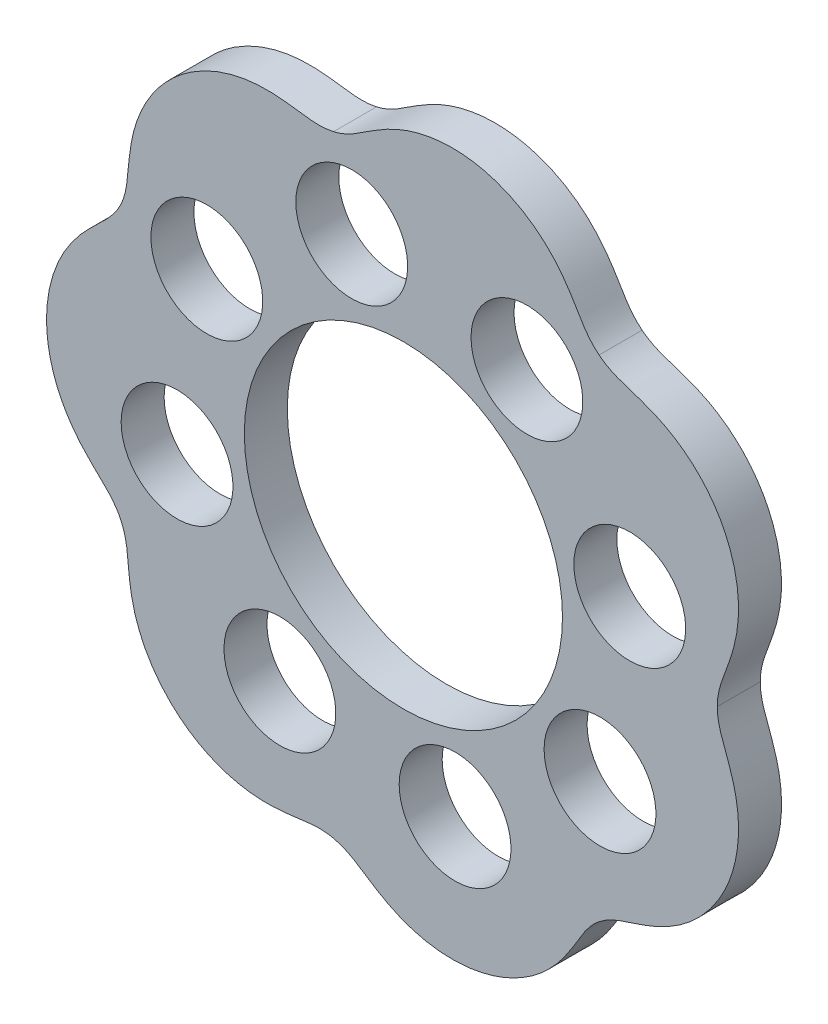
SolidWorks part; units mm, degrees
material "5052-H34"
ref_plane "Front Plane" through (0, 0, 0) normal (0, 0, 1) x (1, 0, 0)
ref_plane "Top Plane" through (0, 0, 0) normal (0, 1, 0) x (1, 0, 0)
ref_plane "Right Plane" through (0, 0, 0) normal (1, 0, 0) x (0, 0, -1)
sketch "Sketch1" plane through (0, 0, 0) normal (0, 0, 1) x (1, 0, 0)
  line L0 (0, 0) -> (37, 0) construction
  line L2 (37, 0) -> (39.5, 0) construction
  line L5 (24.6278, 30.8823) -> (0, 0) construction
  line L6 (0, 0) -> (-8.7896, 38.5096) construction
  line L7 (-35.5883, 17.1384) -> (0, 0) construction
  line L9 (-35.5883, -17.1384) -> (0, 0) construction
  line L10 (-8.7896, -38.5097) -> (0, 0) construction
  line L11 (24.6278, -30.8823) -> (0, 0) construction
  circle A0 centre (0, 0) radius 36 construction
  circle A1 centre (37, 0) radius 6 construction
  spline S0 degree 4 poles (39.9483, -2.12) (39.9195, -2.0383) (39.8632, -1.8746) (39.7822, -1.6278) (39.6848, -1.2955) (39.6113, -0.995) (39.5602, -0.7266) (39.5276, -0.4967) (39.5088, -0.2963) (39.4998, -0.0928) (39.4991, 0.0501) (39.505, 0.2155) (39.5157, 0.3724) (39.5329, 0.5353) (39.558, 0.7077) (39.6011, 0.9443) (39.6734, 1.255) (39.779, 1.6227) (39.9203, 2.0472) (40.0768, 2.4805) (40.3026, 3.083) (40.5945, 3.8559) (41.0315, 5.0877) (41.5249, 6.8077) (41.9013, 8.8642) (42.0339, 11.2502) (41.8633, 13.6337) (41.3936, 15.9767) (40.6339, 18.2422) (39.5972, 20.395) (38.2996, 22.4015) (36.7607, 24.2296) (35.0035, 25.849) (33.2989, 27.0601) (31.7392, 27.9386) (30.3866, 28.5643) (29.2788, 29.0047) (28.3249, 29.3341) (27.5386, 29.5876) (26.9268, 29.7867) (26.4905, 29.9345) (26.0706, 30.0887) (25.717, 30.2355) (25.4294, 30.3725) (25.184, 30.5045) (25.0052, 30.6109) (24.8304, 30.7289) (24.6664, 30.8504) (24.5552, 30.94) (24.4016, 31.074) (24.2567, 31.2136) (24.0973, 31.3824) (23.9194, 31.5897) (23.7303, 31.8345) (23.5312, 32.1179) (23.3886, 32.3351) (23.2958, 32.4812) (23.2499, 32.5546) knots 0 0 0 0 0 0.00783 0.015661 0.023491 0.031321 0.035802 0.040282 0.044763 0.049243 0.052611 0.055979 0.059347 0.062715 0.06731 0.071905 0.081096 0.091513 0.101931 0.112349 0.122766 0.149711 0.176657 0.230547 0.284438 0.338328 0.392219 0.446109 0.5 0.553891 0.607781 0.661672 0.715562 0.769453 0.796398 0.823343 0.850289 0.877234 0.887651 0.898069 0.908487 0.918904 0.928095 0.93269 0.937285 0.944021 0.947389 0.950757 0.955237 0.959718 0.964198 0.968679 0.976509 0.984339 0.99217 1 1 1 1 1 construction
  spline S1 degree 4 poles (39.5, 0) (39.5, 0.0336) (39.5009, 0.1009) (39.505, 0.2155) (39.5157, 0.3724) (39.5329, 0.5353) (39.558, 0.7077) (39.6011, 0.9443) (39.6734, 1.255) (39.779, 1.6227) (39.9203, 2.0472) (40.0768, 2.4805) (40.3026, 3.083) (40.5945, 3.8559) (41.0315, 5.0877) (41.5249, 6.8077) (41.9013, 8.8642) (42.0339, 11.2502) (41.8633, 13.6337) (41.3936, 15.9767) (40.6339, 18.2422) (39.5972, 20.395) (38.2996, 22.4015) (36.7607, 24.2296) (35.0035, 25.849) (33.2989, 27.0601) (31.7392, 27.9386) (30.3866, 28.5643) (29.2788, 29.0047) (28.3249, 29.3341) (27.5386, 29.5876) (26.9268, 29.7867) (26.4905, 29.9345) (26.0706, 30.0887) (25.717, 30.2355) (25.4294, 30.3725) (25.184, 30.5045) (25.0052, 30.6109) (24.8304, 30.7289) (24.7073, 30.8201) (24.6541, 30.8614) (24.6278, 30.8823) knots 0.049243 0.049243 0.049243 0.049243 0.049243 0.052611 0.055979 0.059347 0.062715 0.06731 0.071905 0.081096 0.091513 0.101931 0.112349 0.122766 0.149711 0.176657 0.230547 0.284438 0.338328 0.392219 0.446109 0.5 0.553891 0.607781 0.661672 0.715562 0.769453 0.796398 0.823343 0.850289 0.877234 0.887651 0.898069 0.908487 0.918904 0.928095 0.93269 0.937285 0.944021 0.947389 0.950757 0.950757 0.950757 0.950757 0.950757 construction
  spline S2 degree 4 poles (23.2499, -32.5546) (23.2958, -32.4812) (23.3886, -32.3351) (23.5312, -32.1179) (23.7303, -31.8345) (23.9194, -31.5897) (24.0973, -31.3824) (24.2568, -31.2136) (24.4016, -31.074) (24.5552, -30.9401) (24.6665, -30.8504) (24.7994, -30.7519) (24.9287, -30.6624) (25.0669, -30.5743) (25.2173, -30.4865) (25.4292, -30.3727) (25.7171, -30.2354) (26.0705, -30.0887) (26.4905, -29.9345) (26.9268, -29.7867) (27.5387, -29.5876) (28.3249, -29.334) (29.5605, -28.9076) (31.2128, -28.2209) (33.0554, -27.233) (35.0035, -25.8491) (36.7607, -24.2296) (38.2996, -22.4016) (39.5971, -20.395) (40.6339, -18.2422) (41.3936, -15.9767) (41.8634, -13.6337) (42.0339, -11.2502) (41.9179, -9.1625) (41.6323, -7.3953) (41.2783, -5.9477) (40.9318, -4.807) (40.5946, -3.8558) (40.3026, -3.083) (40.0768, -2.4805) (39.9203, -2.0472) (39.779, -1.6228) (39.6734, -1.2549) (39.6011, -0.9446) (39.5513, -0.6704) (39.523, -0.4642) (39.5063, -0.254) (39.4991, -0.05) (39.4998, 0.0928) (39.5088, 0.2963) (39.5276, 0.4967) (39.5602, 0.7266) (39.6113, 0.995) (39.6848, 1.2955) (39.7822, 1.6278) (39.8632, 1.8746) (39.9195, 2.0383) (39.9483, 2.12) knots 0 0 0 0 0 0.00783 0.015661 0.023491 0.031321 0.035802 0.040282 0.044763 0.049243 0.052611 0.055979 0.059347 0.062715 0.06731 0.071905 0.081096 0.091513 0.101931 0.112349 0.122766 0.149711 0.176657 0.230547 0.284438 0.338328 0.392219 0.446109 0.5 0.553891 0.607781 0.661672 0.715562 0.769453 0.796398 0.823343 0.850289 0.877234 0.887651 0.898069 0.908487 0.918904 0.928095 0.93269 0.937285 0.944021 0.947389 0.950757 0.955237 0.959718 0.964198 0.968679 0.976509 0.984339 0.99217 1 1 1 1 1 construction
  spline S3 degree 4 poles (24.6278, -30.8823) (24.6541, -30.8614) (24.7073, -30.8201) (24.7994, -30.7519) (24.9287, -30.6624) (25.0669, -30.5743) (25.2173, -30.4865) (25.4292, -30.3727) (25.7171, -30.2354) (26.0705, -30.0887) (26.4905, -29.9345) (26.9268, -29.7867) (27.5387, -29.5876) (28.3249, -29.334) (29.5605, -28.9076) (31.2128, -28.2209) (33.0554, -27.233) (35.0035, -25.8491) (36.7607, -24.2296) (38.2996, -22.4016) (39.5971, -20.395) (40.6339, -18.2422) (41.3936, -15.9767) (41.8634, -13.6337) (42.0339, -11.2502) (41.9179, -9.1625) (41.6323, -7.3953) (41.2783, -5.9477) (40.9318, -4.807) (40.5946, -3.8558) (40.3026, -3.083) (40.0768, -2.4805) (39.9203, -2.0472) (39.779, -1.6228) (39.6734, -1.2549) (39.6011, -0.9446) (39.5513, -0.6704) (39.523, -0.4642) (39.5063, -0.254) (39.5009, -0.1009) (39.5, -0.0336) (39.5, 0) knots 0.049243 0.049243 0.049243 0.049243 0.049243 0.052611 0.055979 0.059347 0.062715 0.06731 0.071905 0.081096 0.091513 0.101931 0.112349 0.122766 0.149711 0.176657 0.230547 0.284438 0.338328 0.392219 0.446109 0.5 0.553891 0.607781 0.661672 0.715562 0.769453 0.796398 0.823343 0.850289 0.877234 0.887651 0.898069 0.908487 0.918904 0.928095 0.93269 0.937285 0.944021 0.947389 0.950757 0.950757 0.950757 0.950757 0.950757 construction
  spline S4 degree 4 poles (-10.9562, -38.475) (-10.8702, -38.4651) (-10.698, -38.4466) (-10.4393, -38.4226) (-10.0937, -38.4016) (-9.7844, -38.3968) (-9.5114, -38.4066) (-9.2799, -38.426) (-9.0804, -38.4523) (-8.88, -38.4888) (-8.7405, -38.5199) (-8.5806, -38.5624) (-8.43, -38.6078) (-8.275, -38.6609) (-8.1126, -38.7237) (-7.8915, -38.8184) (-7.6046, -38.9579) (-7.2696, -39.1427) (-6.8872, -39.375) (-6.4996, -39.6239) (-5.9625, -39.9782) (-5.2739, -40.4348) (-4.1702, -41.1349) (-2.6031, -41.9986) (-0.6819, -42.8232) (1.6147, -43.4834) (3.9765, -43.8475) (6.3652, -43.911) (8.7429, -43.6744) (11.0725, -43.1427) (13.3174, -42.3241) (15.4421, -41.2306) (17.4119, -39.8778) (18.9719, -38.4855) (20.1754, -37.1604) (21.0865, -35.981) (21.7623, -34.9989) (22.2957, -34.1422) (22.7178, -33.432) (23.0481, -32.8798) (23.2893, -32.4874) (23.5331, -32.1123) (23.7549, -31.8003) (23.9524, -31.5503) (24.1357, -31.3404) (24.2793, -31.1898) (24.4332, -31.0457) (24.5882, -30.9128) (24.7002, -30.8243) (24.865, -30.7045) (25.0333, -30.5943) (25.2335, -30.4763) (25.4752, -30.3491) (25.7559, -30.2191) (26.0764, -30.0881) (26.3199, -29.9975) (26.4831, -29.9395) (26.5648, -29.9111) knots 0 0 0 0 0 0.00783 0.015661 0.023491 0.031321 0.035802 0.040282 0.044763 0.049243 0.052611 0.055979 0.059347 0.062715 0.06731 0.071905 0.081096 0.091513 0.101931 0.112349 0.122766 0.149711 0.176657 0.230547 0.284438 0.338328 0.392219 0.446109 0.5 0.553891 0.607781 0.661672 0.715562 0.769453 0.796398 0.823343 0.850289 0.877234 0.887651 0.898069 0.908487 0.918904 0.928095 0.93269 0.937285 0.944021 0.947389 0.950757 0.955237 0.959718 0.964198 0.968679 0.976509 0.984339 0.99217 1 1 1 1 1 construction
  spline S5 degree 4 poles (-8.7896, -38.5097) (-8.7568, -38.5171) (-8.6914, -38.533) (-8.5806, -38.5624) (-8.43, -38.6078) (-8.275, -38.6609) (-8.1126, -38.7237) (-7.8915, -38.8184) (-7.6046, -38.9579) (-7.2696, -39.1427) (-6.8872, -39.375) (-6.4996, -39.6239) (-5.9625, -39.9782) (-5.2739, -40.4348) (-4.1702, -41.1349) (-2.6031, -41.9986) (-0.6819, -42.8232) (1.6147, -43.4834) (3.9765, -43.8475) (6.3652, -43.911) (8.7429, -43.6744) (11.0725, -43.1427) (13.3174, -42.3241) (15.4421, -41.2306) (17.4119, -39.8778) (18.9719, -38.4855) (20.1754, -37.1604) (21.0865, -35.981) (21.7623, -34.9989) (22.2957, -34.1422) (22.7178, -33.432) (23.0481, -32.8798) (23.2893, -32.4874) (23.5331, -32.1123) (23.7549, -31.8003) (23.9524, -31.5503) (24.1357, -31.3404) (24.2793, -31.1898) (24.4332, -31.0457) (24.5495, -30.946) (24.6016, -30.9033) (24.6278, -30.8823) knots 0.049243 0.049243 0.049243 0.049243 0.049243 0.052611 0.055979 0.059347 0.062715 0.06731 0.071905 0.081096 0.091513 0.101931 0.112349 0.122766 0.149711 0.176657 0.230547 0.284438 0.338328 0.392219 0.446109 0.5 0.553891 0.607781 0.661672 0.715562 0.769453 0.796398 0.823343 0.850289 0.877234 0.887651 0.898069 0.908487 0.918904 0.928095 0.93269 0.937285 0.944021 0.947389 0.950757 0.950757 0.950757 0.950757 0.950757 construction
  spline S6 degree 4 poles (-36.912, -15.4229) (-36.8506, -15.484) (-36.7288, -15.607) (-36.5488, -15.7943) (-36.3169, -16.0514) (-36.1203, -16.2903) (-35.9578, -16.5098) (-35.8286, -16.7029) (-35.7247, -16.8752) (-35.6284, -17.0547) (-35.5657, -17.1832) (-35.4992, -17.3347) (-35.4408, -17.4807) (-35.3857, -17.635) (-35.3335, -17.8012) (-35.2697, -18.0331) (-35.1999, -18.3443) (-35.1356, -18.7215) (-35.0787, -19.1653) (-35.0317, -19.6235) (-34.9737, -20.2643) (-34.9014, -21.0873) (-34.7606, -22.3868) (-34.4588, -24.1505) (-33.9057, -26.1667) (-32.99, -28.3739) (-31.8021, -30.4474) (-30.3624, -32.3545) (-28.6949, -34.066) (-26.8267, -35.5559) (-24.7871, -36.8007) (-22.6074, -37.78) (-20.3215, -38.4766) (-18.2604, -38.8281) (-16.474, -38.9429) (-14.9838, -38.9199) (-13.7946, -38.8359) (-12.7923, -38.7188) (-11.9739, -38.606) (-11.3362, -38.52) (-10.879, -38.4639) (-10.4338, -38.4206) (-10.0516, -38.3994) (-9.733, -38.3981) (-9.4546, -38.4105) (-9.2473, -38.4288) (-9.0386, -38.4593) (-8.8382, -38.4976) (-8.6991, -38.5301) (-8.5026, -38.5841) (-8.3115, -38.6471) (-8.0946, -38.73) (-7.8443, -38.8396) (-7.5677, -38.9781) (-7.2654, -39.147) (-7.0428, -39.2809) (-6.8957, -39.3722) (-6.8225, -39.4185) knots 0 0 0 0 0 0.00783 0.015661 0.023491 0.031321 0.035802 0.040282 0.044763 0.049243 0.052611 0.055979 0.059347 0.062715 0.06731 0.071905 0.081096 0.091513 0.101931 0.112349 0.122766 0.149711 0.176657 0.230547 0.284438 0.338328 0.392219 0.446109 0.5 0.553891 0.607781 0.661672 0.715562 0.769453 0.796398 0.823343 0.850289 0.877234 0.887651 0.898069 0.908487 0.918904 0.928095 0.93269 0.937285 0.944021 0.947389 0.950757 0.955237 0.959718 0.964198 0.968679 0.976509 0.984339 0.99217 1 1 1 1 1 construction
  spline S7 degree 4 poles (-35.5883, -17.1384) (-35.5737, -17.1687) (-35.5453, -17.2297) (-35.4992, -17.3347) (-35.4408, -17.4807) (-35.3857, -17.635) (-35.3335, -17.8012) (-35.2697, -18.0331) (-35.1999, -18.3443) (-35.1356, -18.7215) (-35.0787, -19.1653) (-35.0317, -19.6235) (-34.9737, -20.2643) (-34.9014, -21.0873) (-34.7606, -22.3868) (-34.4588, -24.1505) (-33.9057, -26.1667) (-32.99, -28.3739) (-31.8021, -30.4474) (-30.3624, -32.3545) (-28.6949, -34.066) (-26.8267, -35.5559) (-24.7871, -36.8007) (-22.6074, -37.78) (-20.3215, -38.4766) (-18.2604, -38.8281) (-16.474, -38.9429) (-14.9838, -38.9199) (-13.7946, -38.8359) (-12.7923, -38.7188) (-11.9739, -38.606) (-11.3362, -38.52) (-10.879, -38.4639) (-10.4338, -38.4206) (-10.0516, -38.3994) (-9.733, -38.3981) (-9.4546, -38.4105) (-9.2473, -38.4288) (-9.0386, -38.4593) (-8.8882, -38.4881) (-8.8223, -38.5022) (-8.7896, -38.5097) knots 0.049243 0.049243 0.049243 0.049243 0.049243 0.052611 0.055979 0.059347 0.062715 0.06731 0.071905 0.081096 0.091513 0.101931 0.112349 0.122766 0.149711 0.176657 0.230547 0.284438 0.338328 0.392219 0.446109 0.5 0.553891 0.607781 0.661672 0.715562 0.769453 0.796398 0.823343 0.850289 0.877234 0.887651 0.898069 0.908487 0.918904 0.928095 0.93269 0.937285 0.944021 0.947389 0.950757 0.950757 0.950757 0.950757 0.950757 construction
  spline S8 degree 4 poles (-35.0725, 19.243) (-35.0819, 19.1569) (-35.1022, 18.985) (-35.1364, 18.7274) (-35.1928, 18.3858) (-35.257, 18.0831) (-35.3273, 17.8192) (-35.3977, 17.5978) (-35.4677, 17.4092) (-35.5479, 17.2219) (-35.6093, 17.0929) (-35.6863, 16.9464) (-35.764, 16.8097) (-35.8503, 16.6704) (-35.9477, 16.526) (-36.0892, 16.3315) (-36.2891, 16.0829) (-36.5438, 15.7974) (-36.8553, 15.4763) (-37.1842, 15.1538) (-37.6491, 14.7089) (-38.2475, 14.1393) (-39.1757, 13.219) (-40.3664, 11.8834) (-41.5979, 10.1939) (-42.7526, 8.1018) (-43.6331, 5.8802) (-44.2264, 3.5655) (-44.5249, 1.1947) (-44.5249, -1.1948) (-44.2264, -3.5655) (-43.6331, -5.8803) (-42.7525, -8.1018) (-41.7422, -9.9324) (-40.7182, -11.4006) (-39.771, -12.5513) (-38.9639, -13.4287) (-38.2475, -14.1394) (-37.649, -14.7089) (-37.1842, -15.1538) (-36.8552, -15.4763) (-36.5438, -15.7974) (-36.2889, -16.083) (-36.0892, -16.3313) (-35.9254, -16.5567) (-35.8105, -16.7302) (-35.7042, -16.9123) (-35.6092, -17.0929) (-35.5478, -17.2219) (-35.4676, -17.4092) (-35.3976, -17.5978) (-35.3272, -17.8192) (-35.2569, -18.0831) (-35.1927, -18.3858) (-35.1363, -18.7274) (-35.1021, -18.985) (-35.0818, -19.1569) (-35.0724, -19.243) knots 0 0 0 0 0 0.00783 0.015661 0.023491 0.031321 0.035802 0.040282 0.044763 0.049243 0.052611 0.055979 0.059347 0.062715 0.06731 0.071905 0.081096 0.091513 0.101931 0.112349 0.122766 0.149711 0.176657 0.230547 0.284438 0.338328 0.392219 0.446109 0.5 0.553891 0.607781 0.661672 0.715562 0.769453 0.796398 0.823343 0.850289 0.877234 0.887651 0.898069 0.908487 0.918904 0.928095 0.93269 0.937285 0.944021 0.947389 0.950757 0.955237 0.959718 0.964198 0.968679 0.976509 0.984339 0.99217 1 1 1 1 1 construction
  spline S9 degree 4 poles (-35.5883, 17.1384) (-35.6029, 17.1082) (-35.6329, 17.0479) (-35.6863, 16.9464) (-35.764, 16.8097) (-35.8503, 16.6704) (-35.9477, 16.526) (-36.0892, 16.3315) (-36.2891, 16.0829) (-36.5438, 15.7974) (-36.8553, 15.4763) (-37.1842, 15.1538) (-37.6491, 14.7089) (-38.2475, 14.1393) (-39.1757, 13.219) (-40.3664, 11.8834) (-41.5979, 10.1939) (-42.7526, 8.1018) (-43.6331, 5.8802) (-44.2264, 3.5655) (-44.5249, 1.1947) (-44.5249, -1.1948) (-44.2264, -3.5655) (-43.6331, -5.8803) (-42.7525, -8.1018) (-41.7422, -9.9324) (-40.7182, -11.4006) (-39.771, -12.5513) (-38.9639, -13.4287) (-38.2475, -14.1394) (-37.649, -14.7089) (-37.1842, -15.1538) (-36.8552, -15.4763) (-36.5438, -15.7974) (-36.2889, -16.083) (-36.0892, -16.3313) (-35.9254, -16.5567) (-35.8105, -16.7302) (-35.7042, -16.9123) (-35.6329, -17.0479) (-35.6028, -17.1082) (-35.5883, -17.1384) knots 0.049243 0.049243 0.049243 0.049243 0.049243 0.052611 0.055979 0.059347 0.062715 0.06731 0.071905 0.081096 0.091513 0.101931 0.112349 0.122766 0.149711 0.176657 0.230547 0.284438 0.338328 0.392219 0.446109 0.5 0.553891 0.607781 0.661672 0.715562 0.769453 0.796398 0.823343 0.850289 0.877234 0.887651 0.898069 0.908487 0.918904 0.928095 0.93269 0.937285 0.944021 0.947389 0.950757 0.950757 0.950757 0.950757 0.950757 construction
  spline S10 degree 4 poles (-6.8225, 39.4184) (-6.8957, 39.3722) (-7.0428, 39.2808) (-7.2654, 39.1469) (-7.5677, 38.978) (-7.8444, 38.8395) (-8.0946, 38.7299) (-8.3115, 38.647) (-8.5027, 38.5841) (-8.6991, 38.53) (-8.8382, 38.4976) (-9.0008, 38.4665) (-9.1561, 38.442) (-9.3188, 38.4226) (-9.4924, 38.4087) (-9.7327, 38.3981) (-10.0517, 38.3993) (-10.4337, 38.4205) (-10.879, 38.4638) (-11.3362, 38.5199) (-11.9739, 38.606) (-12.7923, 38.7187) (-14.0905, 38.8706) (-15.8772, 38.9688) (-17.9659, 38.8782) (-20.3216, 38.4766) (-22.6074, 37.7799) (-24.7871, 36.8006) (-26.8267, 35.5558) (-28.6949, 34.066) (-30.3624, 32.3545) (-31.8022, 30.4474) (-32.99, 28.3739) (-33.7914, 26.4426) (-34.3008, 24.7266) (-34.6099, 23.2686) (-34.7927, 22.0906) (-34.9016, 21.0873) (-34.9737, 20.2643) (-35.0318, 19.6235) (-35.0788, 19.1652) (-35.1356, 18.7215) (-35.2001, 18.3442) (-35.2696, 18.0333) (-35.3437, 17.7647) (-35.4077, 17.5667) (-35.4838, 17.37) (-35.5658, 17.1831) (-35.6284, 17.0547) (-35.7248, 16.8752) (-35.8287, 16.7029) (-35.9578, 16.5098) (-36.1204, 16.2903) (-36.3169, 16.0514) (-36.5489, 15.7943) (-36.7289, 15.607) (-36.8507, 15.484) (-36.9121, 15.4229) knots 0 0 0 0 0 0.00783 0.015661 0.023491 0.031321 0.035802 0.040282 0.044763 0.049243 0.052611 0.055979 0.059347 0.062715 0.06731 0.071905 0.081096 0.091513 0.101931 0.112349 0.122766 0.149711 0.176657 0.230547 0.284438 0.338328 0.392219 0.446109 0.5 0.553891 0.607781 0.661672 0.715562 0.769453 0.796398 0.823343 0.850289 0.877234 0.887651 0.898069 0.908487 0.918904 0.928095 0.93269 0.937285 0.944021 0.947389 0.950757 0.955237 0.959718 0.964198 0.968679 0.976509 0.984339 0.99217 1 1 1 1 1 construction
  spline S11 degree 4 poles (-8.7896, 38.5096) (-8.8223, 38.5021) (-8.8882, 38.488) (-9.0008, 38.4665) (-9.1561, 38.442) (-9.3188, 38.4226) (-9.4924, 38.4087) (-9.7327, 38.3981) (-10.0517, 38.3993) (-10.4337, 38.4205) (-10.879, 38.4638) (-11.3362, 38.5199) (-11.9739, 38.606) (-12.7923, 38.7187) (-14.0905, 38.8706) (-15.8772, 38.9688) (-17.9659, 38.8782) (-20.3216, 38.4766) (-22.6074, 37.7799) (-24.7871, 36.8006) (-26.8267, 35.5558) (-28.6949, 34.066) (-30.3624, 32.3545) (-31.8022, 30.4474) (-32.99, 28.3739) (-33.7914, 26.4426) (-34.3008, 24.7266) (-34.6099, 23.2686) (-34.7927, 22.0906) (-34.9016, 21.0873) (-34.9737, 20.2643) (-35.0318, 19.6235) (-35.0788, 19.1652) (-35.1356, 18.7215) (-35.2001, 18.3442) (-35.2696, 18.0333) (-35.3437, 17.7647) (-35.4077, 17.5667) (-35.4838, 17.37) (-35.5454, 17.2297) (-35.5738, 17.1687) (-35.5883, 17.1384) knots 0.049243 0.049243 0.049243 0.049243 0.049243 0.052611 0.055979 0.059347 0.062715 0.06731 0.071905 0.081096 0.091513 0.101931 0.112349 0.122766 0.149711 0.176657 0.230547 0.284438 0.338328 0.392219 0.446109 0.5 0.553891 0.607781 0.661672 0.715562 0.769453 0.796398 0.823343 0.850289 0.877234 0.887651 0.898069 0.908487 0.918904 0.928095 0.93269 0.937285 0.944021 0.947389 0.950757 0.950757 0.950757 0.950757 0.950757 construction
  spline S12 degree 4 poles (26.5648, 29.9111) (26.4831, 29.9395) (26.3199, 29.9975) (26.0764, 30.0881) (25.7559, 30.2191) (25.4752, 30.3491) (25.2335, 30.4763) (25.0333, 30.5943) (24.865, 30.7045) (24.7003, 30.8243) (24.5881, 30.9129) (24.4624, 31.0206) (24.3465, 31.1268) (24.2299, 31.2418) (24.1107, 31.3689) (23.9526, 31.5502) (23.7547, 31.8004) (23.5331, 32.1122) (23.2893, 32.4874) (23.0481, 32.8798) (22.7179, 33.4321) (22.2956, 34.1422) (21.605, 35.2519) (20.5678, 36.71) (19.1947, 38.2865) (17.412, 39.8778) (15.4421, 41.2306) (13.3174, 42.3241) (11.0725, 43.1427) (8.7429, 43.6744) (6.3651, 43.9109) (3.9764, 43.8475) (1.6147, 43.4834) (-0.3949, 42.9058) (-2.0542, 42.2341) (-3.3868, 41.5668) (-4.4218, 40.9751) (-5.274, 40.4348) (-5.9624, 39.9781) (-6.4996, 39.6239) (-6.8872, 39.3749) (-7.2696, 39.1427) (-7.6048, 38.9578) (-7.8912, 38.8184) (-8.1475, 38.7088) (-8.3421, 38.6354) (-8.5433, 38.5723) (-8.7406, 38.5198) (-8.88, 38.4887) (-9.0804, 38.4522) (-9.2799, 38.426) (-9.5114, 38.4066) (-9.7844, 38.3967) (-10.0937, 38.4015) (-10.4393, 38.4225) (-10.698, 38.4465) (-10.8702, 38.465) (-10.9562, 38.4749) knots 0 0 0 0 0 0.00783 0.015661 0.023491 0.031321 0.035802 0.040282 0.044763 0.049243 0.052611 0.055979 0.059347 0.062715 0.06731 0.071905 0.081096 0.091513 0.101931 0.112349 0.122766 0.149711 0.176657 0.230547 0.284438 0.338328 0.392219 0.446109 0.5 0.553891 0.607781 0.661672 0.715562 0.769453 0.796398 0.823343 0.850289 0.877234 0.887651 0.898069 0.908487 0.918904 0.928095 0.93269 0.937285 0.944021 0.947389 0.950757 0.955237 0.959718 0.964198 0.968679 0.976509 0.984339 0.99217 1 1 1 1 1 construction
  spline S13 degree 4 poles (24.6278, 30.8823) (24.6016, 30.9033) (24.5495, 30.946) (24.4624, 31.0206) (24.3465, 31.1268) (24.2299, 31.2418) (24.1107, 31.3689) (23.9526, 31.5502) (23.7547, 31.8004) (23.5331, 32.1122) (23.2893, 32.4874) (23.0481, 32.8798) (22.7179, 33.4321) (22.2956, 34.1422) (21.605, 35.2519) (20.5678, 36.71) (19.1947, 38.2865) (17.412, 39.8778) (15.4421, 41.2306) (13.3174, 42.3241) (11.0725, 43.1427) (8.7429, 43.6744) (6.3651, 43.9109) (3.9764, 43.8475) (1.6147, 43.4834) (-0.3949, 42.9058) (-2.0542, 42.2341) (-3.3868, 41.5668) (-4.4218, 40.9751) (-5.274, 40.4348) (-5.9624, 39.9781) (-6.4996, 39.6239) (-6.8872, 39.3749) (-7.2696, 39.1427) (-7.6048, 38.9578) (-7.8912, 38.8184) (-8.1475, 38.7088) (-8.3421, 38.6354) (-8.5433, 38.5723) (-8.6914, 38.5329) (-8.7569, 38.5171) (-8.7896, 38.5096) knots 0.049243 0.049243 0.049243 0.049243 0.049243 0.052611 0.055979 0.059347 0.062715 0.06731 0.071905 0.081096 0.091513 0.101931 0.112349 0.122766 0.149711 0.176657 0.230547 0.284438 0.338328 0.392219 0.446109 0.5 0.553891 0.607781 0.661672 0.715562 0.769453 0.796398 0.823343 0.850289 0.877234 0.887651 0.898069 0.908487 0.918904 0.928095 0.93269 0.937285 0.944021 0.947389 0.950757 0.950757 0.950757 0.950757 0.950757 construction
  spline S14 degree 1 poles (22.7574, -28.5368) (36.5, 0) knots 0 0 1 1 construction
  spline S15 degree 1 poles (36.5, 0) (22.7574, 28.5368) knots 0 0 1 1 construction
  spline S16 degree 1 poles (22.7574, 28.5368) (-8.122, 35.5848) knots 0 0 1 1 construction
  spline S17 degree 1 poles (-8.122, 35.5848) (-32.8854, 15.8368) knots 0 0 1 1 construction
  spline S18 degree 1 poles (-32.8854, 15.8368) (-32.8854, -15.8368) knots 0 0 1 1 construction
  spline S19 degree 1 poles (-32.8854, -15.8368) (-8.122, -35.5849) knots 0 0 1 1 construction
  spline S20 degree 1 poles (-8.122, -35.5849) (22.7574, -28.5368) knots 0 0 1 1 construction
  spline S21 degree 3 poles (22.7574, -28.5368) (22.8939, -28.428) (23.1702, -28.2236) (23.7922, -27.8312) (24.4834, -27.4927) (25.2467, -27.1904) (26.1429, -26.883) (27.1232, -26.5727) (28.1933, -26.2047) (29.2024, -25.8042) (30.4901, -25.2061) (32.0033, -24.3212) (33.6599, -23.033) (35.6234, -21.0378) (37.5563, -18.0861) (38.6589, -14.7346) (38.9945, -11.9555) (38.9689, -9.8573) (38.7171, -8.1222) (38.3821, -6.7429) (38.0658, -5.7039) (37.6865, -4.6382) (37.3178, -3.6779) (36.9994, -2.7859) (36.7599, -1.9999) (36.5939, -1.2519) (36.5125, -0.5178) (36.5, -0.1747) (36.5, 0) knots 0.049243 0.049243 0.049243 0.049243 0.056286 0.063329 0.077415 0.091501 0.105587 0.13376 0.161932 0.190104 0.218277 0.274621 0.330966 0.387311 0.5 0.612689 0.669034 0.725379 0.781723 0.809896 0.838068 0.86624 0.894413 0.908499 0.922585 0.936671 0.943714 0.950757 0.950757 0.950757 0.950757
  spline S22 degree 3 poles (36.5, 0) (36.5, 0.1747) (36.5125, 0.5181) (36.5935, 1.249) (36.7599, 2.0005) (36.9994, 2.7857) (37.3178, 3.6781) (37.6864, 4.6379) (38.0659, 5.7041) (38.382, 6.7427) (38.7172, 8.1224) (38.9688, 9.8572) (38.9946, 11.9555) (38.6588, 14.7346) (37.5563, 18.0861) (35.6234, 21.0378) (33.6599, 23.033) (32.0034, 24.3212) (30.4899, 25.2061) (29.2026, 25.8042) (28.1931, 26.2047) (27.1235, 26.5726) (26.1428, 26.8831) (25.2469, 27.1903) (24.483, 27.4931) (23.7946, 27.8297) (23.17, 28.2238) (22.894, 28.4279) (22.7574, 28.5368) knots 0.049243 0.049243 0.049243 0.049243 0.056286 0.063329 0.077415 0.091501 0.105587 0.13376 0.161932 0.190104 0.218277 0.274621 0.330966 0.387311 0.5 0.612689 0.669034 0.725379 0.781723 0.809896 0.838068 0.86624 0.894413 0.908499 0.922585 0.936671 0.943714 0.950757 0.950757 0.950757 0.950757
  spline S23 degree 3 poles (22.7574, 28.5368) (22.6208, 28.6457) (22.3601, 28.8696) (21.8391, 29.3887) (21.3554, 29.9873) (20.8908, 30.6642) (20.3916, 31.4695) (19.871, 32.3561) (19.2741, 33.3175) (18.6591, 34.2122) (17.7894, 35.3346) (16.59, 36.6129) (14.9655, 37.9413) (12.5834, 39.4116) (9.2756, 40.6392) (5.7627, 40.9683) (2.9787, 40.6772) (0.9387, 40.1853) (-0.6969, 39.5536) (-1.967, 38.9201) (-2.9096, 38.3805) (-3.8642, 37.7737) (-4.7183, 37.2005) (-5.5171, 36.6916) (-6.2301, 36.2832) (-6.9224, 35.9549) (-7.62, 35.7122) (-7.9517, 35.6237) (-8.122, 35.5848) knots 0.049243 0.049243 0.049243 0.049243 0.056286 0.063329 0.077415 0.091501 0.105587 0.13376 0.161932 0.190104 0.218277 0.274621 0.330966 0.387311 0.5 0.612689 0.669034 0.725379 0.781723 0.809896 0.838068 0.86624 0.894413 0.908499 0.922585 0.936671 0.943714 0.950757 0.950757 0.950757 0.950757
  spline S24 degree 3 poles (-8.122, 35.5848) (-8.2923, 35.5459) (-8.6299, 35.4817) (-9.3605, 35.398) (-10.1302, 35.393) (-10.949, 35.4518) (-11.8899, 35.5636) (-12.9077, 35.7094) (-14.0315, 35.8422) (-15.1145, 35.9192) (-16.5342, 35.939) (-18.2815, 35.7983) (-20.3329, 35.3565) (-22.9676, 34.4108) (-25.9898, 32.5901) (-28.4374, 30.0489) (-29.9456, 27.6907) (-30.8329, 25.7891) (-31.3589, 24.1165) (-31.6555, 22.7285) (-31.8213, 21.6551) (-31.942, 20.5304) (-32.0264, 19.5053) (-32.1266, 18.5635) (-32.2518, 17.7514) (-32.4268, 17.0054) (-32.672, 16.3087) (-32.8096, 15.9942) (-32.8854, 15.8368) knots 0.049243 0.049243 0.049243 0.049243 0.056286 0.063329 0.077415 0.091501 0.105587 0.13376 0.161932 0.190104 0.218277 0.274621 0.330966 0.387311 0.5 0.612689 0.669034 0.725378 0.781723 0.809895 0.838068 0.86624 0.894412 0.908499 0.922585 0.936671 0.943714 0.950757 0.950757 0.950757 0.950757
  spline S25 degree 3 poles (-32.8854, 15.8368) (-32.9612, 15.6794) (-33.1215, 15.3754) (-33.5116, 14.752) (-33.9875, 14.1471) (-34.544, 13.5436) (-35.2181, 12.8777) (-35.9667, 12.1729) (-36.7711, 11.377) (-37.5066, 10.5783) (-38.4072, 9.4807) (-39.3866, 8.0269) (-40.3203, 6.1475) (-41.2236, 3.498) (-41.6843, 0) (-41.2236, -3.498) (-40.3202, -6.1475) (-39.3867, -8.0269) (-38.407, -9.4809) (-37.5067, -10.5782) (-36.7709, -11.3771) (-35.9668, -12.1727) (-35.2179, -12.8779) (-34.5441, -13.5434) (-33.9872, -14.1476) (-33.5131, -14.7496) (-33.1213, -15.3757) (-32.9612, -15.6793) (-32.8854, -15.8368) knots 0.049243 0.049243 0.049243 0.049243 0.056286 0.063329 0.077415 0.091501 0.105588 0.13376 0.161932 0.190105 0.218277 0.274621 0.330966 0.387311 0.5 0.612689 0.669034 0.725379 0.781723 0.809896 0.838068 0.86624 0.894413 0.908499 0.922585 0.936671 0.943714 0.950757 0.950757 0.950757 0.950757
  spline S26 degree 3 poles (-32.8854, -15.8368) (-32.8096, -15.9941) (-32.6718, -16.309) (-32.4277, -17.0027) (-32.2515, -17.7519) (-32.1266, -18.5633) (-32.0263, -19.5054) (-31.942, -20.5302) (-31.8213, -21.6553) (-31.6554, -22.7283) (-31.3588, -24.1168) (-30.8328, -25.789) (-29.9456, -27.6907) (-28.4373, -30.0489) (-25.9897, -32.5901) (-22.9676, -34.4109) (-20.3329, -35.3565) (-18.2815, -35.7984) (-16.5339, -35.939) (-15.1147, -35.9193) (-14.0313, -35.8421) (-12.908, -35.7096) (-11.8897, -35.5637) (-10.9492, -35.4518) (-10.1296, -35.3932) (-9.3634, -35.3978) (-8.6296, -35.4818) (-8.2923, -35.546) (-8.122, -35.5849) knots 0.049243 0.049243 0.049243 0.049243 0.056286 0.063329 0.077415 0.091501 0.105587 0.13376 0.161932 0.190104 0.218277 0.274621 0.330966 0.387311 0.5 0.612689 0.669034 0.725379 0.781723 0.809896 0.838068 0.86624 0.894413 0.908499 0.922585 0.936671 0.943714 0.950757 0.950757 0.950757 0.950757
  spline S27 degree 3 poles (-8.122, -35.5849) (-7.9517, -35.6237) (-7.6197, -35.7124) (-6.9251, -35.954) (-6.2295, -36.2834) (-5.5172, -36.6916) (-4.7181, -37.2006) (-3.8644, -37.7736) (-2.9094, -38.3808) (-1.9671, -38.92) (-0.6966, -39.5539) (0.9387, -40.1852) (2.9787, -40.6773) (5.7628, -40.9683) (9.2756, -40.6392) (12.5834, -39.4116) (14.9655, -37.9413) (16.59, -36.613) (17.7895, -35.3343) (18.659, -34.2124) (19.2741, -33.3173) (19.8709, -32.3564) (20.3917, -31.4694) (20.8906, -30.6643) (21.3558, -29.9869) (21.8372, -29.3907) (22.3603, -28.8694) (22.6208, -28.6458) (22.7574, -28.5368) knots 0.049243 0.049243 0.049243 0.049243 0.056286 0.063329 0.077415 0.091501 0.105587 0.13376 0.161932 0.190104 0.218277 0.274621 0.330966 0.387311 0.5 0.612689 0.669034 0.725379 0.781723 0.809896 0.838068 0.86624 0.894413 0.908499 0.922585 0.936671 0.943714 0.950757 0.950757 0.950757 0.950757
  point P24 (0, 0)
  point P28 (0, 0)
  point P29 (0, 0)
  point P30 (0, 0)
  point P32 (0, 0)
  point P33 (0, 0)
  point P35 (0, 0)
  point P43 (0, 0)
  point P46 (0, 0)
  point P54 (0, 0)
  dimension "a" = 72
  dimension "b" = 12
  dimension "c" = 2.5
  dimension "D1" = 3
extrude "Boss-Extrude1" add sketch "Sketch1" against normal blind 5
sketch "ｽｹｯﾁ2" plane through (0, 0, -5) normal (0, 0, -1) x (-1, 0, 0)
  line L0 (0, 0) -> (8.7896, 38.5096) construction
  line L1 (0, 0) -> (6.0081, 26.323) construction
  circle A0 centre (0, 0) radius 27 construction
  circle A1 centre (6.0081, 26.323) radius 6.5
  circle A2 centre (22.8616, 14.3648) radius 6.5
  circle A3 centre (26.323, -6.0081) radius 6.5
  circle A4 centre (14.3648, -22.8616) radius 6.5
  circle A5 centre (-6.0081, -26.323) radius 6.5
  circle A6 centre (-22.8616, -14.3648) radius 6.5
  circle A7 centre (-26.323, 6.0081) radius 6.5
  circle A8 centre (-14.3648, 22.8616) radius 6.5
  circle A10 centre (0, 0) radius 18.5
  point P23 (0, 0)
  point P24 (-1.3687, -6.0081)
  point P25 (-0.6862, -3.0066)
  dimension "D1" = 54
  dimension "D2" = 13
  dimension "D4" = 37
  dimension "D5" = 0
  dimension "D3" = 8
extrude "ｶｯﾄ - 押し出し1" cut sketch "ｽｹｯﾁ2" against normal through all
equation "\"a\"= 72"
equation "\"b\"= 12"
equation "\"r\"= 3"
equation "\"m\"= 7"
equation "\"a@Sketch1\"= \"a\""
equation "\"b@Sketch1\"= \"b\""
equation "\"c\"= 2.5"
equation "\"c@Sketch1\"= \"c\""
